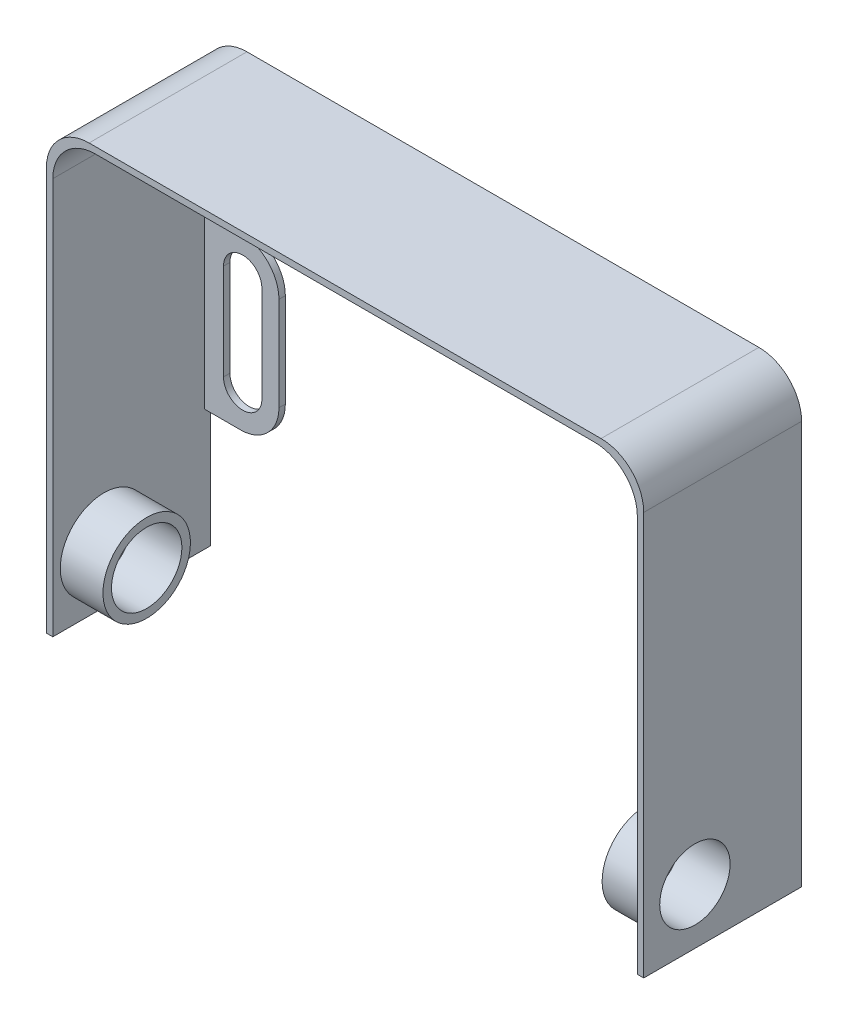
SolidWorks part; units mm, degrees
ref_plane "Ebene vorne" through (0, 0, 0) normal (0, 0, 1) x (1, 0, 0)
ref_plane "Ebene oben" through (0, 0, 0) normal (0, 1, 0) x (1, 0, 0)
ref_plane "Ebene rechts" through (0, 0, 0) normal (1, 0, 0) x (0, 0, -1)
sketch "Skizze1" plane through (0, 0, 0) normal (0, 0, 1) x (1, 0, 0)
  line L1 (0, 0) -> (140, 0)
  line L2 (0, 0) -> (0, 209.01)
  line L3 (0, 209.01) -> (140, 209.01)
  line L4 (140, 0) -> (140, 209.01)
  line L5 (1.5, 207.51) -> (138.5, 207.51)
  line L6 (1.5, 207.51) -> (1.5, 1.5)
  line L7 (1.5, 1.5) -> (138.5, 1.5)
  line L8 (138.5, 207.51) -> (138.5, 1.5)
  dimension "D1" = 140
  dimension "D2" = 209.01
  dimension "D3" = 1.5
  dimension "D4" = 1.5
  dimension "D5" = 1.5
  dimension "D6" = 1.5
extrude "Aufsatz-Linear austragen1" add sketch "Skizze1" along normal blind 37
fillet "Verrundung1" radius 10 8 edges at (140, 0, 18.5) (1.5, 207.51, 18.5) (140, 209.01, 18.5) (0, 209.01, 18.5) (0, 0, 18.5) (1.5, 1.5, 18.5) (138.5, 1.5, 18.5) (138.5, 207.51, 18.5)
sketch "Skizze4" plane through (140, 0, 0) normal (1, 0, 0) x (0, 0, -1)
  line L0 (-37, 104.505) -> (0, 104.505) construction
  line L1 (-37, 10) -> (-37, 199.01) construction
  line L2 (0, 10) -> (0, 199.01) construction
  circle A0 centre (-25, 117.505) radius 8.25
  circle A1 centre (-25, 91.505) radius 8.25
  dimension "D2" = 16.5
  dimension "D1" = 26
  dimension "D3" = 25
extrude "Schnitt-Linear austragen2" cut sketch "Skizze4" against normal through all both and the other way through all
sketch "Skizze5" plane through (0, 0, 0) normal (0, 0, -1) x (-1, 0, 0)
  line L0 (0, 153.01) -> (-19, 153.01) construction
  line L5 (-130, 209.01) -> (-10, 209.01) construction
  line L10 (0, 199.01) -> (0, 10) construction
  line L13 (-70, 209.01) -> (-70, 0) construction
  line L16 (-10, 0) -> (-130, 0) construction
  line L17 (-32.7994, 104.505) -> (-114.9075, 104.505) construction
  line L19 (-140, 153.01) -> (-121, 153.01) construction
  line L20 (-140, 173.01) -> (-130, 173.01)
  line L23 (-140, 173.01) -> (-140, 133.01)
  line L34 (-58.75, 200.32) -> (-81.25, 200.32) construction
  line L35 (-58.75, 204.82) -> (-81.25, 204.82)
  line L36 (-58.75, 195.82) -> (-81.25, 195.82)
  line L37 (-10.5, 164.26) -> (-10.5, 141.76) construction
  line L38 (-15, 164.26) -> (-15, 141.76)
  line L39 (-6, 164.26) -> (-6, 141.76)
  line L40 (-140, 133.01) -> (-130, 133.01)
  line L43 (-121, 164.01) -> (-121, 142.01)
  line L54 (-90, 209.01) -> (-90, 200.82)
  line L55 (-59, 191.82) -> (-81, 191.82)
  line L56 (-50, 209.01) -> (-50, 200.82)
  line L57 (-50, 209.01) -> (-90, 209.01)
  line L58 (-19, 164.01) -> (-19, 142.01)
  line L59 (0, 133.01) -> (-10, 133.01)
  line L60 (0, 173.01) -> (0, 133.01)
  line L61 (0, 173.01) -> (-10, 173.01)
  line L62 (-70, 209.01) -> (-70, 191.82) construction
  line L67 (-129.5, 164.26) -> (-129.5, 141.76) construction
  line L68 (-125, 164.26) -> (-125, 141.76)
  line L69 (-134, 164.26) -> (-134, 141.76)
  line L73 (-10.5, 44.75) -> (-10.5, 67.25) construction
  line L74 (-15, 44.75) -> (-15, 67.25)
  line L75 (-6, 44.75) -> (-6, 67.25)
  line L76 (-129.5, 44.75) -> (-129.5, 67.25) construction
  line L77 (-125, 44.75) -> (-125, 67.25)
  line L78 (-134, 44.75) -> (-134, 67.25)
  line L79 (-140, 56) -> (-121, 56) construction
  line L80 (0, 56) -> (-19, 56) construction
  line L81 (0, 36) -> (-10, 36)
  line L82 (0, 36) -> (0, 76)
  line L83 (0, 76) -> (-10, 76)
  line L84 (-19, 45) -> (-19, 67)
  line L85 (-121, 45) -> (-121, 67)
  line L86 (-140, 76) -> (-130, 76)
  line L87 (-140, 36) -> (-140, 76)
  line L88 (-140, 36) -> (-130, 36)
  arc A8 (-58.75, 204.82) -> (-58.75, 195.82) centre (-58.75, 200.32) cw
  arc A9 (-81.25, 195.82) -> (-81.25, 204.82) centre (-81.25, 200.32) cw
  arc A10 (-15, 164.26) -> (-6, 164.26) centre (-10.5, 164.26) cw
  arc A11 (-6, 141.76) -> (-15, 141.76) centre (-10.5, 141.76) cw
  arc A16 (-90, 200.82) -> (-81, 191.82) centre (-81, 200.82) ccw
  arc A17 (-59, 191.82) -> (-50, 200.82) centre (-59, 200.82) ccw
  arc A18 (-19, 142.01) -> (-10, 133.01) centre (-10, 142.01) ccw
  arc A19 (-19, 164.01) -> (-10, 173.01) centre (-10, 164.01) cw
  arc A20 (-121, 164.01) -> (-130, 173.01) centre (-130, 164.01) ccw
  arc A21 (-121, 142.01) -> (-130, 133.01) centre (-130, 142.01) cw
  arc A24 (-125, 164.26) -> (-134, 164.26) centre (-129.5, 164.26) ccw
  arc A25 (-134, 141.76) -> (-125, 141.76) centre (-129.5, 141.76) ccw
  arc A28 (-15, 44.75) -> (-6, 44.75) centre (-10.5, 44.75) ccw
  arc A29 (-6, 67.25) -> (-15, 67.25) centre (-10.5, 67.25) ccw
  arc A30 (-125, 44.75) -> (-134, 44.75) centre (-129.5, 44.75) cw
  arc A31 (-134, 67.25) -> (-125, 67.25) centre (-129.5, 67.25) cw
  arc A32 (-121, 67) -> (-130, 76) centre (-130, 67) ccw
  arc A33 (-121, 45) -> (-130, 36) centre (-130, 45) cw
  arc A34 (-19, 45) -> (-10, 36) centre (-10, 45) ccw
  arc A35 (-19, 67) -> (-10, 76) centre (-10, 67) cw
  point P42 (-129.5, 153.01)
  point P58 (-70, 200.32)
  point P65 (-10.5, 153.01)
  point P70 (-10.5, 56)
  point P77 (-129.5, 56)
  point P105 (-90, 191.82)
  point P108 (-50, 191.82)
  dimension "D4" = 9
  dimension "D10" = 9
  dimension "D1" = 9
  dimension "D2" = 22.5
  dimension "D3" = 40
  dimension "D6" = 8.69
  dimension "D7" = 9
  dimension "D8" = 22.5
  dimension "D9" = 4
  dimension "D11" = 40
  dimension "D12" = 10.5
  dimension "D13" = 4
  dimension "D14" = 56
  dimension "D15" = 104.505
extrude "Aufsatz-Linear austragen3" add sketch "Skizze5" against normal blind 1.5
sketch "Skizze6" plane through (0, 0, 1.5) normal (0, 0, 1) x (1, 0, 0)
  line L0 (130, 209.01) -> (10, 209.01) construction
  line L1 (-30.9644, 104.505) -> (199.5516, 104.505)
  line L2 (-30.9644, 104.505) -> (-30.9644, -15.0602)
  line L3 (-30.9644, -15.0602) -> (199.5516, -15.0602)
  line L4 (199.5516, 104.505) -> (199.5516, -15.0602)
  dimension "D1" = 104.505
extrude "Schnitt-Linear austragen3" cut sketch "Skizze6" against normal through all both and the other way through all
sketch "Skizze8" plane through (1.5, 0, 0) normal (1, 0, 0) x (0, 0, -1)
  circle A0 centre (-25, 117.505) radius 8.25
  circle A1 centre (-25, 117.505) radius 10.25
  circle A2 centre (-25, 117.505) radius 8.25 construction
  dimension "D1" = 2
extrude "Aufsatz-Linear austragen5" add sketch "Skizze8" along normal blind 10
ref_plane "Ebene1" through (70, 0, 0) normal (-1, 0, 0) x (0, 0, 1)
mirror "Spiegeln1" about plane through (70, 0, 0) normal (-1, 0, 0) of "Aufsatz-Linear austragen5"
